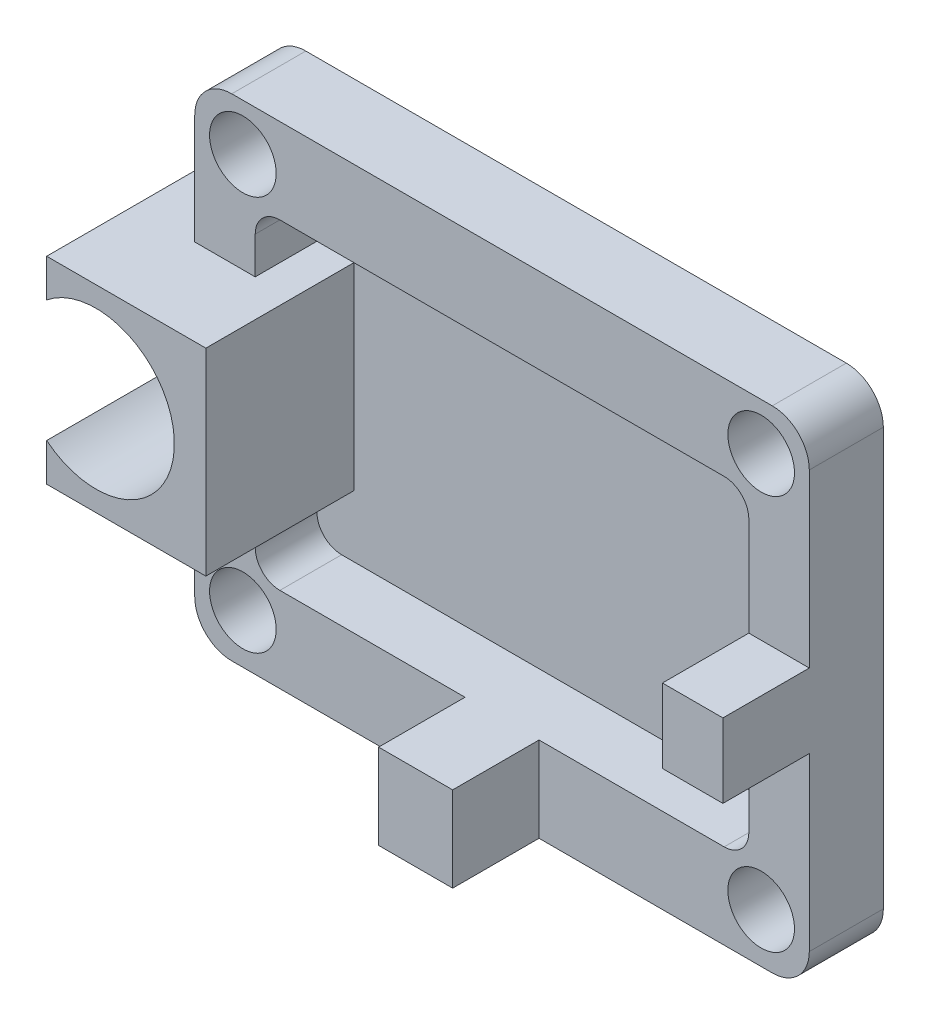
SolidWorks part; units mm, degrees
ref_plane "Alzado" through (0, 0, 0) normal (0, 0, 1) x (1, 0, 0)
ref_plane "Planta" through (0, 0, 0) normal (0, 1, 0) x (1, 0, 0)
ref_plane "Vista lateral" through (0, 0, 0) normal (1, 0, 0) x (0, 0, -1)
sketch "Croquis1" plane through (0, 0, 0) normal (0, 0, 1) x (1, 0, 0)
  line L1 (-56.8634, 16.1421) -> (-7.0634, 16.1421)
  line L2 (-56.8634, 16.1421) -> (-56.8634, -23.6579)
  line L3 (-56.8634, -23.6579) -> (-7.0634, -23.6579)
  line L4 (-7.0634, 16.1421) -> (-7.0634, -23.6579)
  circle A0 centre (-52.9634, 12.3421) radius 2.7
  circle A1 centre (-10.9634, 12.3421) radius 2.7
  circle A2 centre (-10.9634, -19.6579) radius 2.7
  circle A3 centre (-52.9634, -19.6579) radius 2.7
  dimension "D3" = 3.8
  dimension "D7" = 5.4
  dimension "D1" = 49.8
  dimension "D2" = 39.8
  dimension "D4" = 3.9
  dimension "D5" = 2
  dimension "D6" = 2
extrude "Saliente-Extruir1" add sketch "Croquis1" along normal blind 6
sketch "Croquis2" plane through (0, 0, 6) normal (0, 0, 1) x (1, 0, 0)
  line L0 (-56.8634, -23.6579) -> (-7.0634, 16.1421) construction
  line L2 (-49.9634, -16.7579) -> (-13.9634, -16.7579)
  line L3 (-51.9634, -14.7579) -> (-51.9634, 7.2421)
  line L4 (-49.9634, 9.2421) -> (-13.9634, 9.2421)
  line L5 (-11.9634, -14.7579) -> (-11.9634, 7.2421)
  line L6 (-51.9634, -16.7579) -> (-11.9634, 9.2421) construction
  line L7 (-51.9634, 9.2421) -> (-11.9634, -16.7579) construction
  arc A0 (-11.9634, 7.2421) -> (-13.9634, 9.2421) centre (-13.9634, 7.2421) ccw
  arc A1 (-11.9634, -14.7579) -> (-13.9634, -16.7579) centre (-13.9634, -14.7579) cw
  arc A2 (-49.9634, -16.7579) -> (-51.9634, -14.7579) centre (-49.9634, -14.7579) cw
  arc A3 (-49.9634, 9.2421) -> (-51.9634, 7.2421) centre (-49.9634, 7.2421) ccw
  point P4 (-31.9634, -3.7579)
  dimension "D3" = 2
  dimension "D1" = 40
  dimension "D2" = 26
extrude "Cortar-Extruir1" cut sketch "Croquis2" against normal blind 5
sketch "Croquis3" plane through (0, 0, 6) normal (0, 0, 1) x (1, 0, 0)
  line L14 (-7.0634, -3.7579) -> (-7.0634, -0.7579)
  line L15 (-7.0634, -23.6579) -> (-7.0634, 16.1421) construction
  line L16 (-7.0634, -0.7579) -> (-11.9634, -0.7579)
  line L17 (-11.9634, -14.7579) -> (-11.9634, 7.2421) construction
  line L18 (-11.9634, -0.7579) -> (-11.9634, -6.7579)
  line L19 (-11.9634, -6.7579) -> (-7.0634, -6.7579)
  line L20 (-7.0634, -6.7579) -> (-7.0634, -0.7579)
  line L22 (-56.8634, -23.6579) -> (-7.0634, -23.6579) construction
  line L23 (-34.9634, -23.6579) -> (-34.9634, -16.7579)
  line L24 (-49.9634, -16.7579) -> (-13.9634, -16.7579) construction
  line L25 (-34.9634, -16.7579) -> (-28.9634, -16.7579)
  line L26 (-28.9634, -16.7579) -> (-28.9634, -23.6579)
  line L27 (-28.9634, -23.6579) -> (-34.9634, -23.6579)
  line M2 (-11.9634, 7.2421) -> (-11.9634, -14.7579)
  line M4 (-13.9634, -16.7579) -> (-49.9634, -16.7579)
  line M12 (-56.8634, -23.6579) -> (-7.0634, -23.6579)
  line M13 (-7.0634, -23.6579) -> (-7.0634, 16.1421)
extrude "Saliente-Extruir2" add sketch "Croquis3" along normal blind 7 contours L26 L23 M4 M12 | L19 L16 M2 M13
fillet "Redondeo1" radius 3 4 edges at (-56.8634, 16.1421, 3) (-7.0634, 16.1421, 3) (-7.0634, -23.6579, 3) (-56.8634, -23.6579, 3)
sketch "Croquis4" plane through (0, 0, 0) normal (0, 0, -1) x (-1, 0, 0)
  line L1 (56.8634, 13.1421) -> (56.8634, -20.6579) construction
  line L2 (56.8634, 4.2421) -> (61.8634, 4.2421)
  line L4 (61.8634, -11.7579) -> (56.8634, -11.7579)
  line L6 (56.8634, 4.2421) -> (61.8634, -11.7579) construction
  line L7 (57.8634, -0.2579) -> (61.8634, -0.2579)
  line L8 (57.8634, -7.2579) -> (61.8634, -7.2579)
  line L9 (61.8634, 4.2421) -> (61.8634, -0.2579)
  line L10 (61.8634, -7.2579) -> (61.8634, -11.7579)
  line L11 (56.8634, 4.2421) -> (56.8634, -0.4038)
  line L12 (56.8634, -7.112) -> (56.8634, -11.7579)
  arc A2 (57.8634, -0.2579) -> (56.8634, -0.4038) centre (57.8634, -3.7579) ccw
  arc A3 (57.8634, -7.2579) -> (56.8634, -7.112) centre (57.8634, -3.7579) cw
  dimension "D1" = 5
  dimension "D2" = 3.5
  dimension "D3" = 5
extrude "Saliente-Extruir3" add sketch "Croquis4" against normal blind 3
sketch "Croquis5" plane through (0, 0, 3) normal (0, 0, 1) x (1, 0, 0)
  circle A1 centre (-57.8634, -3.7579) radius 6.35
extrude "Cortar-Extruir2" cut sketch "Croquis5" along normal up to vertex (3 mm away)
sketch "Croquis6" plane through (0, 0, 3) normal (0, 0, 1) x (1, 0, 0)
  line L6 (-61.8634, 4.2421) -> (-51.9634, 4.2421)
  line L8 (-51.9634, -11.7579) -> (-61.8634, -11.7579)
  line L9 (-61.8634, 4.2421) -> (-61.8634, 1.1739)
  line L10 (-61.8634, -0.2579) -> (-61.8634, 4.2421) construction
  line L11 (-61.8634, -11.7579) -> (-61.8634, -8.6897)
  line L12 (-51.9634, 4.2421) -> (-48.9634, 4.2421)
  line L13 (-48.9634, 4.2421) -> (-48.9634, -11.7579)
  line L14 (-48.9634, -11.7579) -> (-51.9634, -11.7579)
  arc A5 (-61.8634, 1.1739) -> (-61.8634, -8.6897) centre (-57.8634, -3.7579) cw
extrude "Saliente-Extruir4" add sketch "Croquis6" along normal blind 10
sketch "Croquis7" plane through (0, 0, 1) normal (0, 0, 1) x (1, 0, 0)
  line L0 (-51.9634, -3.7579) -> (-51.9634, 4.2421)
  line L1 (-51.9634, 7.2421) -> (-51.9634, -14.7579) construction
  line L2 (-51.9634, 4.2421) -> (-48.9634, 4.2421)
  line L3 (-48.9634, 4.2421) -> (-48.9634, -11.7579)
  line L4 (-48.9634, -11.7579) -> (-51.9634, -11.7579)
  line L5 (-51.9634, -11.7579) -> (-51.9634, -3.7579)
extrude "Saliente-Extruir5" add sketch "Croquis7" along normal blind 2
sketch "Croquis8" plane through (0, 0, 3) normal (0, 0, 1) x (1, 0, 0)
  line L0 (-56.8634, -0.4038) -> (-56.8634, -7.112)
  arc A0 (-56.8634, -0.4038) -> (-56.8634, -7.112) centre (-56.8634, -3.7579) cw
extrude "Cortar-Extruir3" cut sketch "Croquis8" against normal up to vertex
